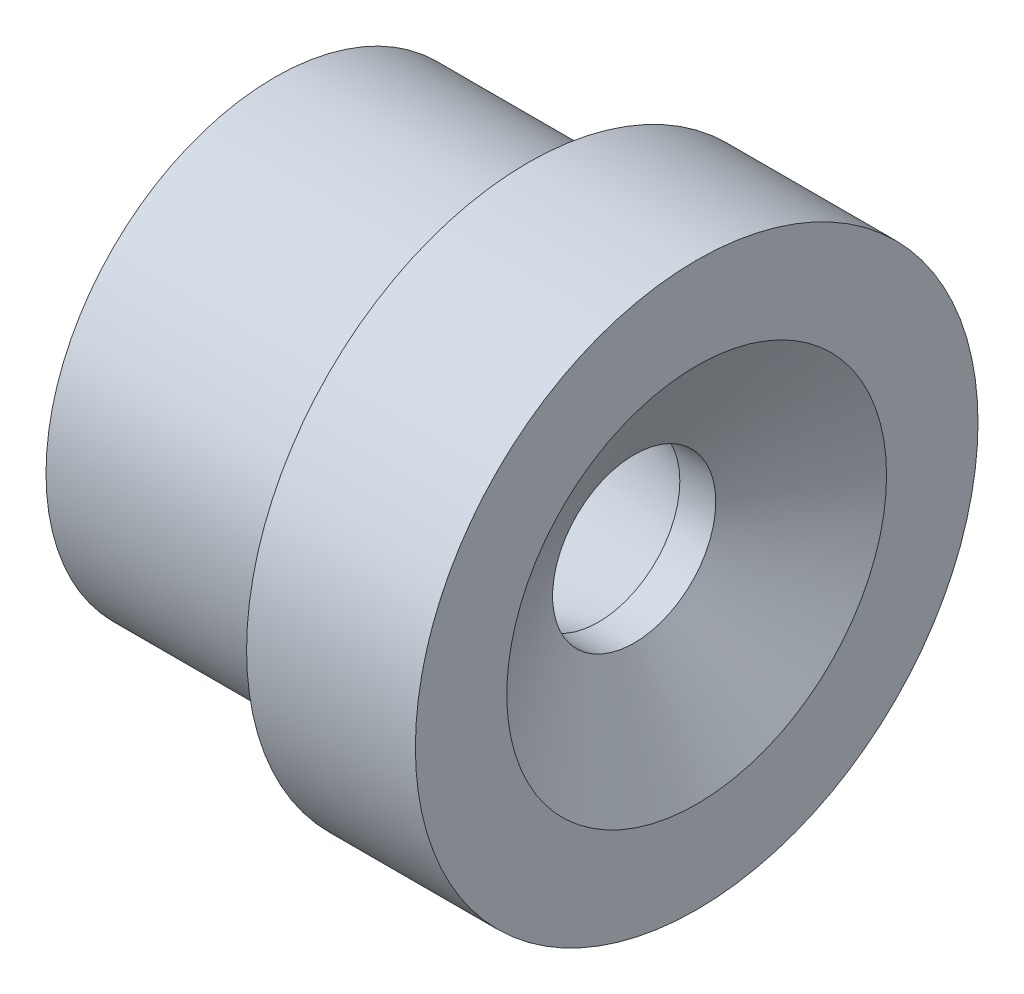
SolidWorks part; units mm, degrees
material "C (Graphite)"
ref_plane "Front Plane" through (0, 0, 0) normal (0, 0, 1) x (1, 0, 0)
ref_plane "Top Plane" through (0, 0, 0) normal (0, 1, 0) x (1, 0, 0)
ref_plane "Right Plane" through (0, 0, 0) normal (1, 0, 0) x (0, 0, -1)
sketch "Sketch1" plane through (0, 0, 0) normal (0, 1, 0) x (1, 0, 0)
  line L0 (0, 0) -> (0, 4.1275)
  line L1 (0, 4.1275) -> (-2.823, 9.017)
  line L2 (-2.823, 9.017) -> (-4.4435, 9.017)
  line L3 (-4.4435, 9.017) -> (-19.05, 5.1032)
  line L4 (-19.05, 5.1032) -> (-19.05, 2.3749)
  line L5 (-19.05, 2.3749) -> (-7.62, 2.3749)
  line L6 (-7.62, 2.3749) -> (-7.62, 0)
  line L9 (-7.62, 0) -> (0, 0)
  line L10 (5.1187, 12.7) -> (-11.0703, 12.7) construction
  dimension "D1" = 25.4
  dimension "D2" = 7.366
  dimension "D3" = 60
  dimension "D4" = 15
  dimension "D5" = 17.145
  dimension "D6" = 1.6205
  dimension "D7" = 7.62
  dimension "D8" = 19.05
  dimension "D9" = 20.6502
revolve "Revolve1" add sketch "Sketch1" angle 360 about L10
